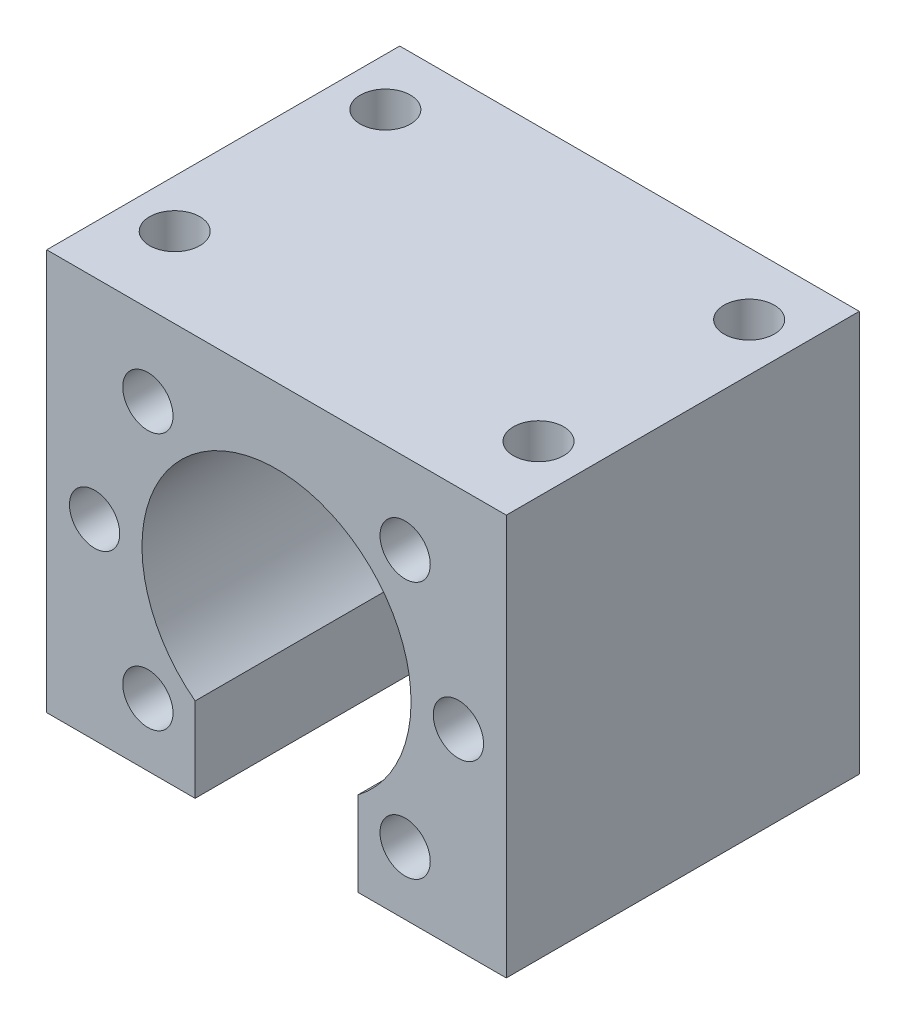
SolidWorks part; units mm, degrees
ref_plane "Front Plane" through (0, 0, 0) normal (0, 0, 1) x (1, 0, 0)
ref_plane "Top Plane" through (0, 0, 0) normal (0, 1, 0) x (1, 0, 0)
ref_plane "Right Plane" through (0, 0, 0) normal (1, 0, 0) x (0, 0, -1)
ref_plane "Plane1"
sketch "Sketch1" plane through (0, 0, 0) normal (0, 0, 1) x (1, 0, 0)
  line L0 (-24, 20) -> (24, 20)
  line L1 (24, 20) -> (24, -20)
  line L2 (24, -20) -> (8.5, -20)
  line L3 (8.5, -20) -> (8.5, -11.1872)
  line L4 (-8.5, -11.1872) -> (-8.5, -20)
  line L5 (-8.5, -20) -> (-24, -20)
  line L6 (-24, -20) -> (-24, 20)
  arc A0 (8.5, -11.1872) -> (-8.5, -11.1872) centre (0, 0) ccw
  dimension "D6" = 14.05
  dimension "D1" = 48
  dimension "D2" = 40
  dimension "D3" = 17
  dimension "D4" = 15.5
  dimension "D5" = 40
  dimension "D7" = 8.8128
extrude "Extrusion1" add sketch "Sketch1" along normal blind 36.8695
hole_wizard "Thread6" positions "Sketch3" profile "Sketch2" legacy
sketch "Sketch3" plane through (0, 0, 36.8695) normal (0, 0, 1) x (1, 0, 0)
  point P1 (-19, 0)
  point P2 (-13.435, -13.435)
  point P3 (-13.435, 13.435)
  point P4 (13.435, 13.435)
  point P5 (19, 0)
  point P6 (13.435, -13.435)
sketch "Sketch2" plane through (-19, 0, 36.8695) normal (1, 0, 0) x (0, -1, 0)
  line L0 (0, 0) -> (0, 21.5773)
  line L1 (0, 21.5773) -> (2.625, 20)
  line L2 (2.625, 20) -> (2.625, 0)
  line L4 (2.625, 0) -> (0, 0)
  line L6 (0, 21.5773) -> (-2.625, 20) construction
  line L7 (0, -4.2442) -> (0, 117.3081) construction
  dimension "Diameter" = 5.25
  dimension "Depth" = 20
  dimension "Drill Angle" = 118
cosmetic thread "Cosmetic Thread1"
cosmetic thread "Cosmetic Thread2"
cosmetic thread "Cosmetic Thread3"
cosmetic thread "Cosmetic Thread4"
cosmetic thread "Cosmetic Thread5"
cosmetic thread "Cosmetic Thread6"
hole_wizard "Thread10" positions "Sketch5" profile "Sketch4" legacy
sketch "Sketch5" plane through (0, 20, 0) normal (0, 1, 0) x (1, 0, 0)
  point P1 (-19, -6.5)
  point P2 (19, -6.5)
  point P3 (-19, -28.5)
  point P4 (19, -28.5)
sketch "Sketch4" plane through (-19, 20, 6.5) normal (1, 0, 0) x (0, 0, 1)
  line L0 (0, 0) -> (0, 17)
  line L1 (0, 17) -> (2.625, 17)
  line L2 (2.625, 17) -> (2.625, 0)
  line L3 (2.625, 0) -> (0, 0)
  line L4 (0, 110) -> (0, -10) construction
  dimension "Diameter" = 5.25
  dimension "Depth" = 17
cosmetic thread "Cosmetic Thread7"
cosmetic thread "Cosmetic Thread8"
cosmetic thread "Cosmetic Thread9"
cosmetic thread "Cosmetic Thread10"
sketch "Sketch6" plane through (0, 20, 0) normal (0, 1, 0) x (-1, 0, 0)
  line L0 (-24, 0) -> (24, 0)
  line L1 (24, 0) -> (24, 36.8695)
  line L2 (24, 36.8695) -> (-24, 36.8695)
  line L3 (-24, 36.8695) -> (-24, 0)
  circle A0 centre (19, 28.5) radius 2.625
  circle A1 centre (19, 6.5) radius 2.625
  circle A2 centre (-19, 6.5) radius 2.625
  circle A3 centre (-19, 28.5) radius 2.625
extrude "Extrusion2" add sketch "Sketch6" along normal blind 1.8695
